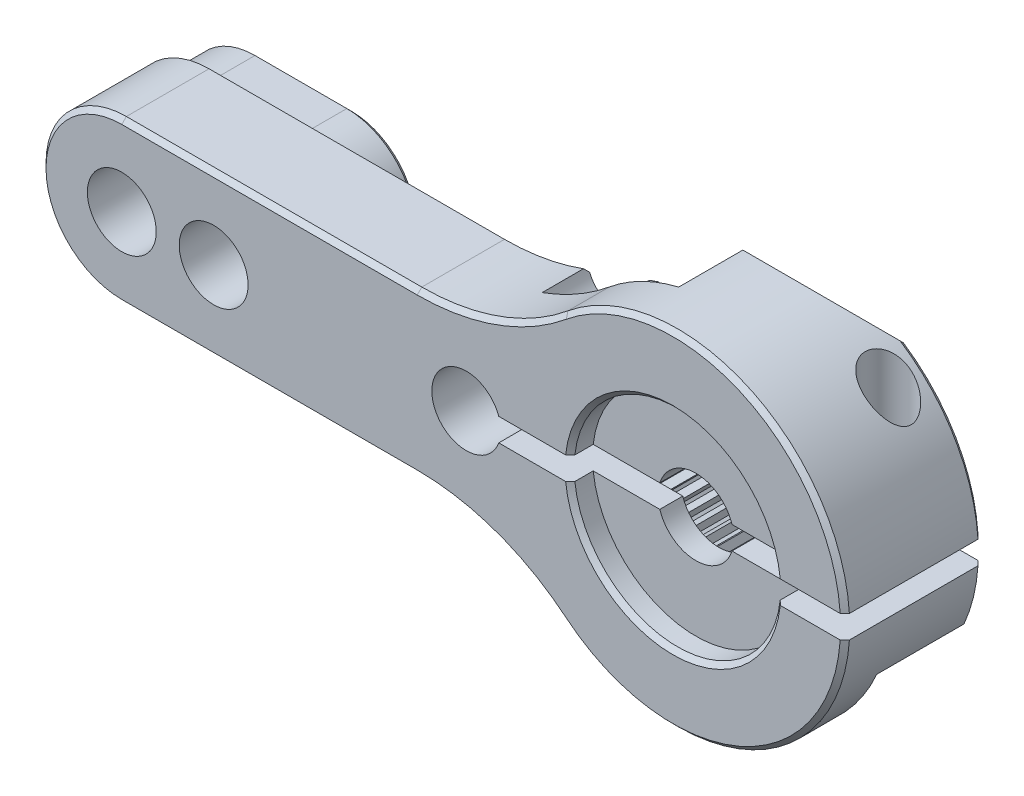
SolidWorks part; units mm, degrees
ref_plane "Plan de face" through (0, 0, 0) normal (0, 0, 1) x (1, 0, 0)
ref_plane "Plan de dessus" through (0, 0, 0) normal (0, 1, 0) x (1, 0, 0)
ref_plane "Plan de droite" through (0, 0, 0) normal (1, 0, 0) x (0, 0, -1)
sketch "Esquisse1" plane through (0, 0, 0) normal (0, 0, 1) x (1, 0, 0)
  line L0 (-11.1355, 3.5) -> (-24, 3.5)
  line L1 (-24, -3.5) -> (-11.1355, -3.5)
  line L2 (0, 0) -> (-40.4273, 0) construction
  line L3 (-27.5, 8.0474) -> (-27.5, -5.9021) construction
  line L4 (7.5, 11.0169) -> (7.5, -8.8025) construction
  circle A1 centre (0, 0) radius 1.65
  arc A2 (-4.7724, 5.7857) -> (-4.7724, -5.7857) centre (0, 0) cw
  arc A3 (-24, 3.5) -> (-24, -3.5) centre (-24, 0) ccw
  arc A4 (-11.1355, -3.5) -> (-4.7724, -5.7857) centre (-11.1355, -13.5) cw
  arc A5 (-4.7724, 5.7857) -> (-11.1355, 3.5) centre (-11.1355, 13.5) cw
  circle A6 centre (-9, 0) radius 1.5
  circle A7 centre (-24, 0) radius 1.5
  circle A8 centre (-20, 0) radius 1.5
  point P14 (-6.6332, -3.5)
  point P18 (-6.6332, 3.5)
  dimension "D1" = 7.5
  dimension "D2" = 3.3
  dimension "D5" = 10
  dimension "D6" = 3
  dimension "D7" = 3
  dimension "D8" = 3
  dimension "D3" = 7
  dimension "D4" = 35
  dimension "D9" = 9
  dimension "D10" = 11
  dimension "D11" = 4
extrude "Boss.-Extru.1" add sketch "Esquisse1" along normal blind 6
sketch "Esquisse2" plane through (0, 0, 6) normal (0, 0, 1) x (1, 0, 0)
  line L0 (7.5, 0) -> (-41.9387, 0) construction
  line L1 (8.5, 0.5) -> (-10.4142, 0.5)
  line L2 (8.5, 0.5) -> (8.5, -0.5)
  line L3 (8.5, -0.5) -> (-10.4142, -0.5)
  line L4 (-10.4142, 0.5) -> (-10.4142, -0.5)
  arc A0 (-4.7724, -5.7857) -> (-4.7724, 5.7857) centre (0, 0) ccw construction
  circle A1 centre (-9, 0) radius 1.5 construction
  dimension "D1" = 1
  dimension "D2" = 1
extrude "Enlèv. mat.-Extru.1" cut sketch "Esquisse2" against normal blind 6
sketch "Esquisse3" plane through (0, 0, 0) normal (0, 0, -1) x (-1, 0, 0)
  line L2 (24, -3.5) -> (11.1355, -3.5)
  line L3 (24, -3.5) -> (11.1355, -3.5)
  line L5 (24, 0) -> (20, 0) construction
  line L6 (11.1355, 3.5) -> (24, 3.5)
  line L7 (11.1355, 3.5) -> (24, 3.5)
  line L8 (24, -3) -> (20, -3)
  line L9 (24, 3) -> (20, 3)
  arc A0 (4.7724, 5.7857) -> (4.7724, -5.7857) centre (0, 0) cw
  arc A5 (11.1355, -3.5) -> (4.7724, -5.7857) centre (11.1355, -13.5) ccw
  arc A6 (11.1355, -3.5) -> (4.7724, -5.7857) centre (11.1355, -13.5) ccw
  arc A10 (24, -3) -> (24, 3) centre (24, 0) ccw
  arc A11 (20, 3) -> (20, -3) centre (20, 0) ccw
  arc A12 (24, -3.5) -> (24, 3.5) centre (24, 0) ccw
  arc A13 (4.7724, 5.7857) -> (11.1355, 3.5) centre (11.1355, 13.5) ccw
  arc A14 (24, -3.5) -> (24, 3.5) centre (24, 0) ccw
  arc A15 (4.7724, 5.7857) -> (11.1355, 3.5) centre (11.1355, 13.5) ccw
  point P5 (22, 0)
  dimension "D3" = 4
  dimension "D4" = 0.5
  dimension "D1" = 0
  dimension "D2" = 0
extrude "Enlèv. mat.-Extru.2" cut sketch "Esquisse3" against normal blind 2
sketch "Esquisse4" plane through (0, 0, 0) normal (0, 0, -1) x (-1, 0, 0)
  line L0 (-7.5, -3) -> (-3.25, -3)
  line L1 (-1.75, -4.5) -> (-1.75, -7.5)
  line L2 (-1.75, -7.5) -> (-7.5, -7.5)
  line L3 (-7.5, -7.5) -> (-7.5, -3)
  line L4 (-1.5724, -0.5) -> (-7.4833, -0.5) construction
  line L5 (1.5724, 0.5) -> (7.4833, 0.5) construction
  line L6 (1.75, 7.5) -> (7.75, 7.5)
  line L7 (1.75, 7.5) -> (1.75, 4.5)
  line L8 (3.25, 3) -> (6.25, 3)
  line L9 (7.75, 7.5) -> (7.75, 4.5)
  arc A0 (7.4833, 0.5) -> (-7.4833, 0.5) centre (0, 0) ccw construction
  arc A1 (-7.4833, -0.5) -> (7.4833, -0.5) centre (0, 0) ccw construction
  arc A2 (-3.25, -3) -> (-1.75, -4.5) centre (-3.25, -4.5) cw
  arc A3 (6.25, 3) -> (7.75, 4.5) centre (6.25, 4.5) ccw
  arc A4 (1.75, 4.5) -> (3.25, 3) centre (3.25, 4.5) ccw
  point P14 (-1.75, -3)
  dimension "D3" = 1.5
  dimension "D7" = 1.5
  dimension "D1" = 5.75
  dimension "D2" = 2.5
  dimension "D4" = 3.5
  dimension "D5" = 2.5
  dimension "D6" = 6
extrude "Enlèv. mat.-Extru.3" cut sketch "Esquisse4" against normal blind 4
sketch "Esquisse5" plane through (0, -3, 0) normal (0, -1, 0) x (1, 0, 0)
  line L0 (3.25, 4) -> (6.8739, 4) construction
  line L2 (6.8739, 4) -> (6.8739, 0) construction
  circle A0 centre (4.8739, 1.5) radius 1
  dimension "D1" = 2
  dimension "D2" = 2.5
  dimension "D3" = 2
extrude "Enlèv. mat.-Extru.4" cut sketch "Esquisse5" against normal through all
sketch "Esquisse6" plane through (0, 3, 0) normal (0, 1, 0) x (1, 0, 0)
  line L0 (-7.4833, -2) -> (-7.4833, 0) construction
  line L1 (4.8739, -1.5) -> (-10.9129, -1.5) construction
  circle A0 centre (-5.2333, -1.5) radius 1
  dimension "D1" = 2
  dimension "D2" = 2.25
extrude "Enlèv. mat.-Extru.5" cut sketch "Esquisse6" against normal through all
sketch "Esquisse7" plane through (0, 0, 0) normal (1, 0, 0) x (0, 0, -1)
  line L0 (-1.4142, 7.5) -> (0, 6.0858)
  line L1 (0, 7.5) -> (-6, 7.5) construction
  line L2 (0, 0.5) -> (0, 7.5) construction
  line L3 (0, 6.0858) -> (0, 7.5)
  line L4 (0, 7.5) -> (-1.4142, 7.5)
  line L5 (0, -6.0858) -> (-1.4142, -7.5)
  line L6 (0, -7.293) -> (0, -4.5) construction
  line L7 (-1.4142, -7.5) -> (0, -7.5)
  line L8 (0, -7.5) -> (0, -6.0858)
  line L9 (0, -7.5) -> (0, -0.5) construction
  dimension "D1" = 2
  dimension "D2" = 45
  dimension "D3" = 45
  dimension "D4" = 2
  dimension "D5" = 15
extrude "Enlèv. mat.-Extru.6" cut sketch "Esquisse7" against normal blind 10 and the other way blind 10
sketch "Esquisse8" plane through (0, 0, 0) normal (0, 0, -1) x (-1, 0, 0)
  circle A0 centre (0, 0) radius 3
  dimension "D1" = 6
extrude "Enlèv. mat.-Extru.7" cut sketch "Esquisse8" against normal blind 4
sketch "Esquisse9" plane through (0, 0, 0) normal (0, 0, -1) x (-1, 0, 0)
  line L0 (0, 0) -> (0, 3.5855) construction
  line L1 (-0.8887, 3) -> (1.1976, 3) construction
  line L2 (-0.2021, 3) -> (0, 2.65)
  line L3 (0, 2.65) -> (0.2021, 3)
  line L4 (0.2021, 3) -> (-0.2021, 3)
  arc A0 (2.958, 0.5) -> (-2.958, 0.5) centre (0, 0) ccw construction
  dimension "D1" = 30
  dimension "D2" = 0.35
extrude "Boss.-Extru.2" add sketch "Esquisse9" against normal up to surface (4 mm away) up to face at (0, 1.4125, 4)
pattern_circular "Répétition circulaire1" count 36 over 360 about axis through (0, 0, 0) along (0, 0, 1) skipping 9, 27 of "Boss.-Extru.2"
sketch "Esquisse10" plane through (0, 0, 0) normal (0, 0, -1) x (-1, 0, 0)
  line L0 (7.4833, -0.5) -> (2.9581, -0.5) construction
  line L1 (-7.4833, 0.5) -> (3.8917, 0.5)
  line L2 (-7.4833, 0.5) -> (-7.4833, -0.5)
  line L3 (-7.4833, -0.5) -> (3.8917, -0.5)
  line L4 (3.8917, 0.5) -> (3.8917, -0.5)
extrude "Enlèv. mat.-Extru.8" cut sketch "Esquisse10" against normal through all
chamfer "Chanfrein1" distance 0.2 angle 45 22 edges at (-22, 3, 0) (-7.2716, 1.8368, 0) (7.2866, -1.7763, 0) (-7.7549, -4.0888, 6) (2.9702, -6.8868, 6) (-8.5271, -3.8462, 2) (-5.6206, -5.1582, 2.422) (-7.7549, 4.0888, 6) (-17.5678, 3.5, 6) (6.5578, 3.6395, 0) (2.9702, 6.8868, 6) (-27.5, 0, 6) (-6.5578, -3.6395, 0) (-17.5678, -3.5, 6) (-9.3901, 3.6535, 2) (-17.5678, 3.5, 2) (-27.5, 0, 2) (-17.5678, -3.5, 2) (-27, 0, 0) (-17, 0, 0)
sketch "Esquisse11" plane through (0, 0, 6) normal (0, 0, 1) x (1, 0, 0)
  circle A0 centre (0, 0) radius 4.5
  dimension "D1" = 9
extrude "Enlèv. mat.-Extru.9" cut sketch "Esquisse11" against normal blind 1
chamfer "Chanfrein2" distance 0.2 angle 45 2 edges at (0, -4.5, 6) (0, 4.5, 6)
